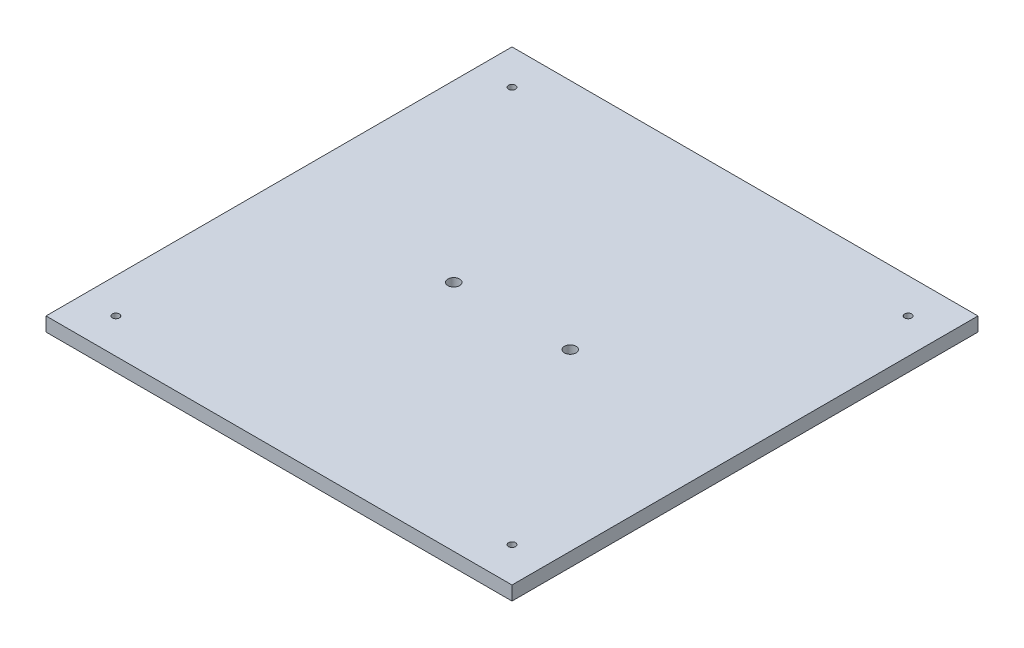
SolidWorks part; units mm, degrees
ref_plane "Front Plane" through (0, 0, 0) normal (0, 0, 1) x (1, 0, 0)
ref_plane "Top Plane" through (0, 0, 0) normal (0, 1, 0) x (1, 0, 0)
ref_plane "Right Plane" through (0, 0, 0) normal (1, 0, 0) x (0, 0, -1)
sketch "Sketch1" plane through (0, 0, 0) normal (0, 1, 0) x (1, 0, 0)
  line L1 (-200, 200) -> (200, 200)
  line L2 (-200, 200) -> (-200, -200)
  line L3 (-200, -200) -> (200, -200)
  line L4 (200, 200) -> (200, -200)
  circle A1 centre (-170, 170) radius 3
  circle A2 centre (170, 170) radius 3
  circle A3 centre (170, -170) radius 3
  circle A4 centre (-170, -170) radius 3
  circle A5 centre (-50, 0) radius 5
  circle A6 centre (50, 0) radius 5
  point P4 (0, 200)
  point P6 (-200, 0)
  point P13 (0, 0)
  point P20 (0, 0)
  point P21 (0, 0)
  dimension "D3" = 50
  dimension "D4" = 6
  dimension "D6" = 10
  dimension "D7" = 10
  dimension "D1" = 400
  dimension "D2" = 400
  dimension "D5" = 100
extrude "Boss-Extrude1" add sketch "Sketch1" along normal blind 12
